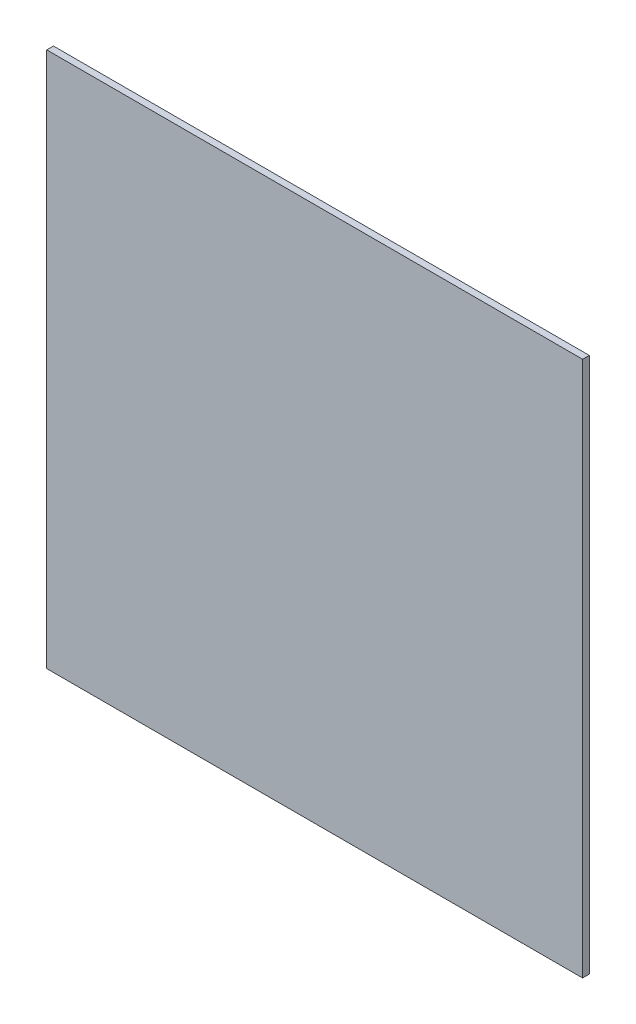
SolidWorks part; units mm, degrees
ref_plane "Plan de face" through (0, 0, 0) normal (0, 0, 1) x (1, 0, 0)
ref_plane "Plan de dessus" through (0, 0, 0) normal (0, 1, 0) x (1, 0, 0)
ref_plane "Plan de droite" through (0, 0, 0) normal (1, 0, 0) x (0, 0, -1)
sketch "Esquisse1" plane through (0, 0, 0) normal (0, 0, 1) x (1, 0, 0)
  line L1 (0, 0) -> (400, 0)
  line L2 (0, 0) -> (0, 400)
  line L3 (0, 400) -> (400, 400)
  line L4 (400, 0) -> (400, 400)
  dimension "D1" = 400
  dimension "D2" = 400
extrude "Boss.-Extru.1" add sketch "Esquisse1" against normal blind 5
